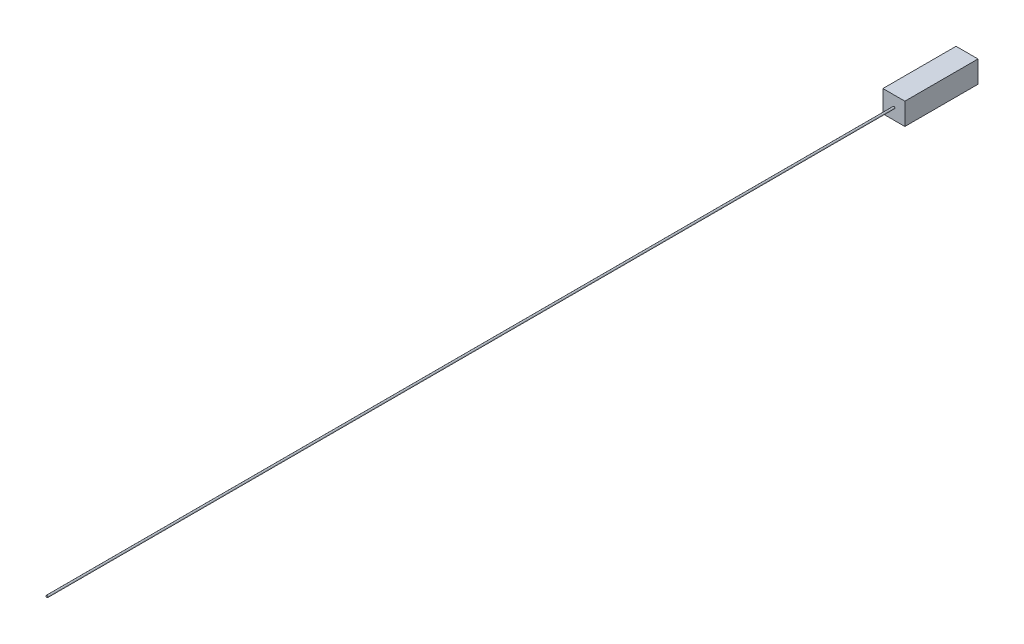
SolidWorks part; units mm, degrees
ref_plane "Plano frontal" through (0, 0, 0) normal (0, 0, 1) x (1, 0, 0)
ref_plane "Plano superior" through (0, 0, 0) normal (0, 1, 0) x (1, 0, 0)
ref_plane "Plano direito" through (0, 0, 0) normal (1, 0, 0) x (0, 0, -1)
sketch "Esboço1" plane through (0, 0, 0) normal (0, 0, 1) x (1, 0, 0)
  line L1 (2.85, 2.85) -> (-2.85, 2.85)
  line L2 (2.85, 2.85) -> (2.85, -2.85)
  line L3 (2.85, -2.85) -> (-2.85, -2.85)
  line L4 (-2.85, 2.85) -> (-2.85, -2.85)
  line L5 (2.85, 2.85) -> (-2.85, -2.85) construction
  line L6 (2.85, -2.85) -> (-2.85, 2.85) construction
  point P0 (0, 0)
  dimension "D1" = 5.7
  dimension "D2" = 5.7
extrude "Ressalto-extrusão1" add sketch "Esboço1" along normal blind 19
sketch "Esboço2" plane through (0, 0, 19) normal (0, 0, 1) x (1, 0, 0)
  circle A0 centre (0, 0) radius 0.25
  dimension "D1" = 0.5
extrude "Ressalto-extrusão2" add sketch "Esboço2" along normal blind 220
